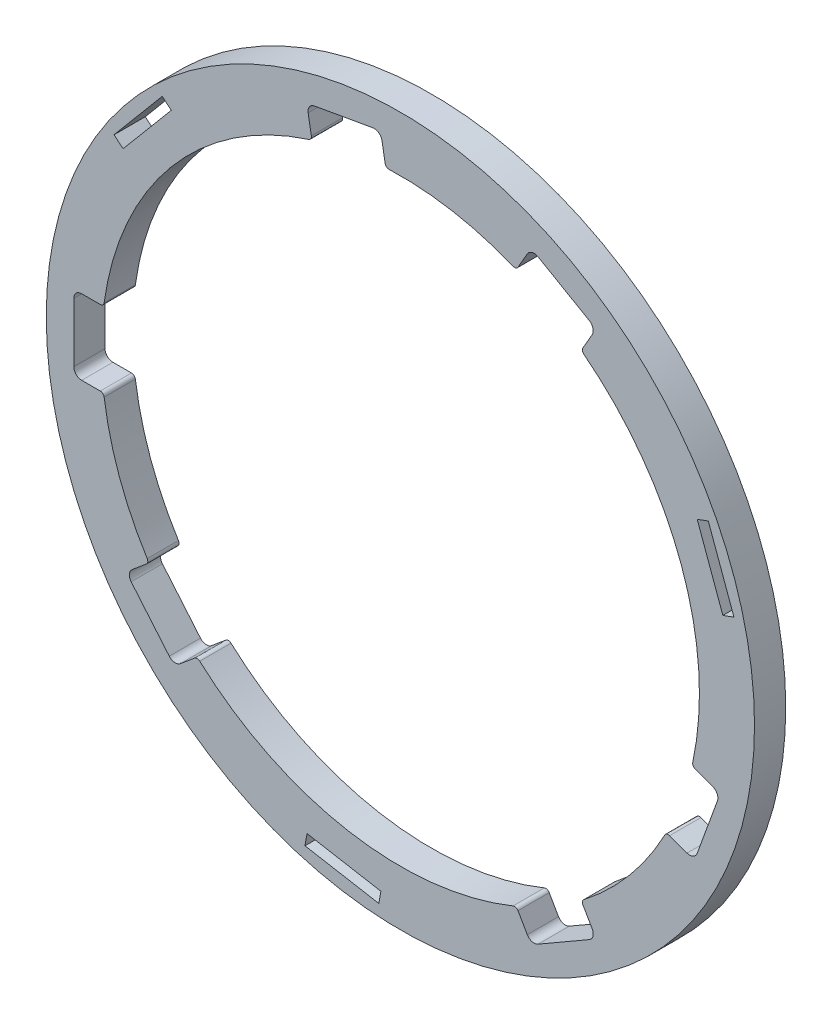
SolidWorks part; units mm, degrees
ref_plane "前基準面" through (0, 0, 0) normal (0, 0, 1) x (1, 0, 0)
ref_plane "上基準面" through (0, 0, 0) normal (0, 1, 0) x (1, 0, 0)
ref_plane "右基準面" through (0, 0, 0) normal (1, 0, 0) x (0, 0, -1)
sketch "Sketch1" plane through (0, 0, 0) normal (0, 0, 1) x (1, 0, 0)
  line L0 (-20.75, -0.0701) -> (-12.75, -0.0701) construction
  line L1 (-16.0869, 13.4285) -> (-0.1915, 0.0906) construction
  line L2 (-3.8381, 20.7716) -> (-0.2349, 0.3368) construction
  line L3 (-20.75, 2.3112) -> (-12.75, 2.3112) construction
  line L4 (-20.75, -2.4513) -> (-12.75, -2.4513) construction
  line L5 (10.2651, 18.5234) -> (-0.1099, 0.5533) construction
  line L6 (19.6236, 7.7358) -> (0.125, 0.6388) construction
  line L7 (19.8585, -6.5436) -> (0.3599, 0.5533) construction
  line L8 (10.8599, -17.6332) -> (0.4849, 0.3368) construction
  line L9 (-3.1617, -20.3441) -> (0.4415, 0.0906) construction
  line L10 (-1.2581, 20.7782) -> (-0.9282, 18.9072)
  line L11 (-1.2581, 20.7782) -> (-5.9483, 19.9512)
  line L12 (-15.6454, -13.4079) -> (0.25, -0.0701) construction
  line L13 (20.3776, 7.474) -> (21.1921, 5.2363)
  line L14 (-14.5563, 15.2526) -> (-15.1308, 15.7347)
  line L15 (-5.9483, 19.9512) -> (-5.6184, 18.0802)
  line L16 (-17.6176, 11.6043) -> (-18.1921, 12.0864)
  line L17 (20.4873, 4.9798) -> (21.1921, 5.2363)
  line L18 (19.6729, 7.2175) -> (20.4873, 4.9798)
  line L19 (18.8584, 9.4551) -> (19.5632, 9.7116)
  line L20 (-22.5, -0.0701) -> (-19, -0.0701) construction
  line L21 (-20.75, -0.0701) -> (0, -0.0701) construction
  line L22 (-20.75, -2.4513) -> (-18.8502, -2.4513)
  line L23 (-20.75, 2.3112) -> (-18.8502, 2.3112)
  line L24 (-20.75, 2.3112) -> (-20.75, -2.4513)
  line L25 (-12.75, 2.3112) -> (-12.75, -2.4513) construction
  line L26 (12.4372, 16.7093) -> (11.4873, 15.064)
  line L27 (12.4372, 16.7093) -> (8.3128, 19.0906)
  line L28 (8.3128, 19.0906) -> (7.3629, 17.4453)
  line L29 (-16.6615, 13.9106) -> (-15.1308, 15.7347)
  line L30 (-16.6615, 13.9106) -> (-18.1921, 12.0864)
  line L31 (-16.0869, 13.4285) -> (-14.5563, 15.2526)
  line L32 (18.6842, -9.4046) -> (16.8989, -8.7549)
  line L33 (18.6842, -9.4046) -> (20.3131, -4.9293)
  line L34 (20.3131, -4.9293) -> (18.5278, -4.2796)
  line L35 (8.3128, -19.2307) -> (7.3629, -17.5854)
  line L36 (8.3128, -19.2307) -> (12.4372, -16.8495)
  line L37 (12.4372, -16.8495) -> (11.4873, -15.2042)
  line L38 (-16.0869, 13.4285) -> (-17.6176, 11.6043)
  line L39 (-16.6615, 13.9106) -> (-15.3607, 15.4607) construction
  line L40 (-16.0869, 13.4285) -> (-14.7862, 14.9787) construction
  line L41 (-17.4261, -11.5838) -> (-15.9707, -10.3626)
  line L42 (-17.4261, -11.5838) -> (-14.3648, -15.2321)
  line L43 (-14.3648, -15.2321) -> (-12.9094, -14.0109)
  line L44 (-14.3648, 15.0919) -> (-12.9094, 13.8707) [skipped]
  line L45 (-14.3648, 15.0919) -> (-17.4261, 11.4436) [skipped]
  line L46 (-17.4261, 11.4436) -> (-15.9707, 10.2225) [skipped]
  line L47 (-5.9483, -20.0913) -> (-5.6184, -18.2204) [skipped]
  line L48 (-5.9483, -20.0913) -> (-1.2581, -20.9183) [skipped]
  line L49 (-1.2581, -20.9183) -> (-0.9282, -19.0474) [skipped]
  line L50 (20.3131, 4.7892) -> (18.6842, 9.2645) [skipped]
  line L51 (18.6842, 9.2645) -> (16.8989, 8.6147) [skipped]
  line L52 (20.3131, 4.7892) -> (18.5278, 4.1394) [skipped]
  line L53 (-16.6615, 13.9106) -> (-18.4274, 11.806) construction
  line L54 (-16.0869, 13.4285) -> (-17.8529, 11.3239) construction
  line L55 (19.6729, 7.2175) -> (18.8584, 9.4551)
  line L56 (20.3776, 7.474) -> (19.5632, 9.7116)
  line L57 (-3.7162, -21.3845) -> (-6.0612, -20.971)
  line L58 (-5.931, -20.2324) -> (-6.0612, -20.971)
  line L59 (-3.5859, -20.6459) -> (-5.931, -20.2324)
  line L60 (-1.2409, -21.0594) -> (-1.3711, -21.798)
  line L61 (-3.5859, -20.6459) -> (-1.2409, -21.0594)
  line L62 (-3.7162, -21.3845) -> (-1.3711, -21.798)
  line L63 (-16.0869, 13.4285) -> (-16.6615, 13.9106) construction
  circle A0 centre (0, -0.0701) radius 22.5
  arc A1 (-18.8502, -2.4513) -> (-15.9707, -10.3626) centre (0, -0.0701) ccw
  circle A2 centre (0, -0.0701) radius 19 construction
  arc A3 (-12.9094, -14.0109) -> (7.3629, -17.5854) centre (0, -0.0701) ccw
  arc A4 (11.4873, -15.2042) -> (16.8989, -8.7549) centre (0, -0.0701) ccw
  arc A5 (18.5278, -4.2796) -> (11.4873, 15.064) centre (0, -0.0701) ccw
  arc A6 (7.3629, 17.4453) -> (-0.9282, 18.9072) centre (0, -0.0701) ccw
  arc A7 (-5.6184, 18.0802) -> (-18.8502, 2.3112) centre (0, -0.0701) ccw
  circle A8 centre (0, -0.0701) radius 21 construction
  circle A9 centre (0, -0.0701) radius 21.75 construction
  point P12 (0, 19)
  dimension "D1" = 3.5
  dimension "D3" = 9
  dimension "D8" = 9
  dimension "D5" = 2.3813
  dimension "D7" = 8
  dimension "D4" = 0.75
  dimension "D9" = 3
  dimension "D10" = 2.3813
  dimension "D12" = 2.3813
  dimension "D6" = 2.3813
  dimension "D2" = 1.5
  dimension "D11" = 0.75
extrude "Boss-Extrude1" add sketch "Sketch1" along normal blind 1.9844
fillet "Fillet1" radius 0.25 12 edges at (-5.6184, 18.0802, 0.9922) (-0.9282, 18.9072, 0.9922) (7.3629, 17.4453, 0.9922) (11.4873, 15.064, 0.9922) (18.5278, -4.2796, 0.9922) (16.8989, -8.7549, 0.9922) (11.4873, -15.2042, 0.9922) (7.3629, -17.5854, 0.9922) (-12.9094, -14.0109, 0.9922) (-15.9707, -10.3626, 0.9922) (-18.8502, -2.4513, 0.9922) (-18.8502, 2.3112, 0.9922)
fillet "Fillet2" radius 0.5 12 edges at (-20.75, 2.3112, 0.9922) (-20.75, -2.4513, 0.9922) (-17.4261, -11.5838, 0.9922) (-14.3648, -15.2321, 0.9922) (8.3128, -19.2307, 0.9922) (12.4372, -16.8495, 0.9922) (18.6842, -9.4046, 0.9922) (20.3131, -4.9293, 0.9922) (12.4372, 16.7093, 0.9922) (8.3128, 19.0906, 0.9922) (-1.2581, 20.7782, 0.9922) (-5.9483, 19.9512, 0.9922)
